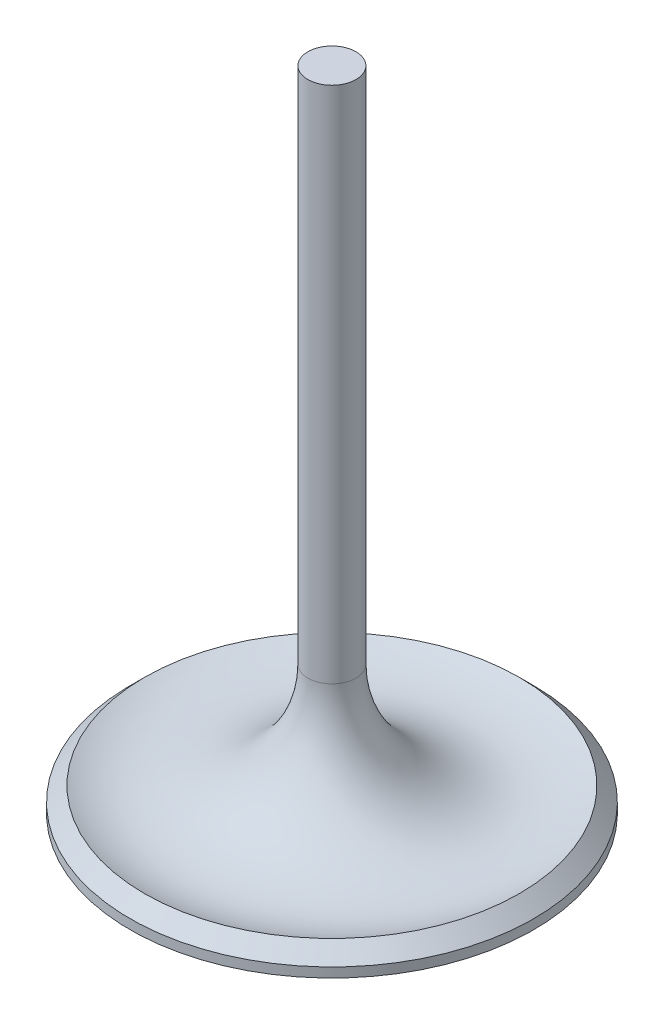
SolidWorks part; units mm, degrees
ref_plane "Front Plane" through (0, 0, 0) normal (0, 0, 1) x (1, 0, 0)
ref_plane "Top Plane" through (0, 0, 0) normal (0, 1, 0) x (1, 0, 0)
ref_plane "Right Plane" through (0, 0, 0) normal (1, 0, 0) x (0, 0, -1)
sketch "Sketch1" plane through (0, 0, 0) normal (0, 0, 1) x (1, 0, 0)
  line L0 (0, 0) -> (0, 85.55)
  line L1 (0, 85.55) -> (3.18, 85.55)
  line L2 (3.18, 85.55) -> (3.18, 17.0542)
  line L3 (24.76, 3.18) -> (26.67, 1.27)
  line L4 (26.67, 1.27) -> (26.67, 0)
  line L5 (26.67, 0) -> (0, 0)
  arc A0 (3.18, 17.0542) -> (24.76, 3.18) centre (18.43, 17.0542) ccw
  dimension "D5" = 15.25
  dimension "D1" = 85.55
  dimension "D2" = 3.18
  dimension "D3" = 26.67
  dimension "D4" = 1.27
  dimension "D6" = 3.18
  dimension "D7" = 45
revolve "Revolve1" add sketch "Sketch1" angle 360 about L0
